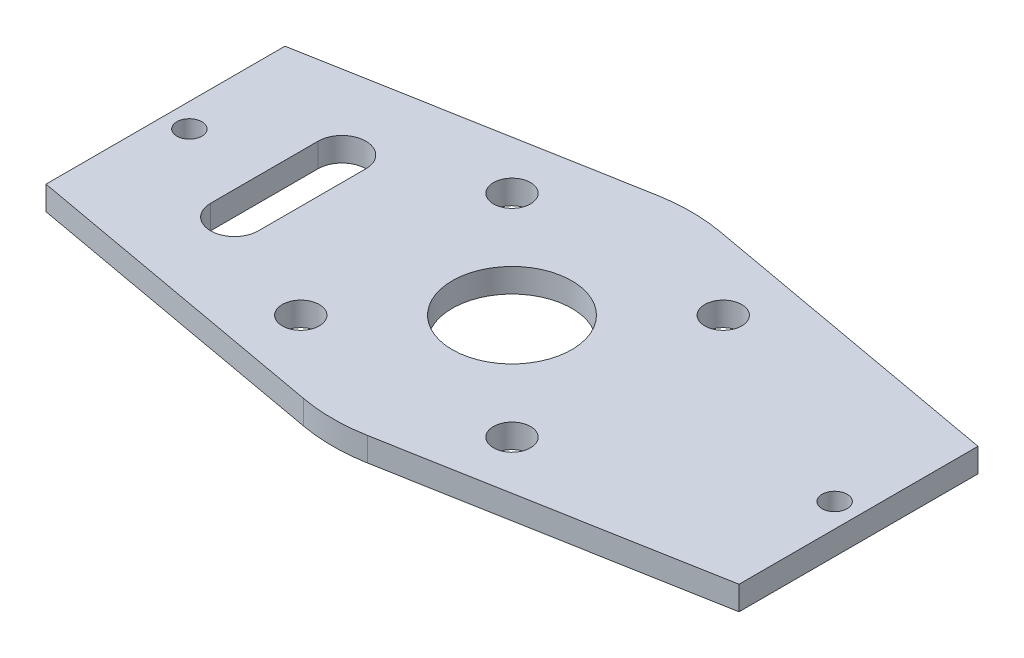
SolidWorks part; units mm, degrees
material "Hexcel AS4C (3000 Filaments)"
ref_plane "Front Plane" through (0, 0, 0) normal (0, 0, 1) x (1, 0, 0)
ref_plane "Top Plane" through (0, 0, 0) normal (0, 1, 0) x (1, 0, 0)
ref_plane "Right Plane" through (0, 0, 0) normal (1, 0, 0) x (0, 0, -1)
sketch "Sketch1" plane through (0, 0, 0) normal (0, 1, 0) x (1, 0, 0)
  line L0 (-2.6687, 14.7607) -> (-29, 10)
  line L1 (2.6687, 14.7607) -> (29, 10)
  line L2 (-2.6687, -14.7607) -> (-29, -10)
  line L4 (-29, 10) -> (-29, -10)
  line L11 (2.6687, -14.7607) -> (29, -10)
  line L12 (29, 10) -> (29, -10)
  line L14 (-18.7281, -4.5) -> (-18.7281, 4.5) construction
  line L15 (-20.7281, -4.5) -> (-20.7281, 4.5)
  line L16 (-16.7281, -4.5) -> (-16.7281, 4.5)
  circle A7 centre (0, 0) radius 5
  circle A8 centre (-27, 0) radius 1.05
  circle A9 centre (27, 0) radius 1.05
  circle A11 centre (8.8388, 8.8388) radius 1.55
  circle A12 centre (8.8388, -8.8388) radius 1.55
  circle A13 centre (-8.8388, -8.8388) radius 1.55
  circle A14 centre (-8.8388, 8.8388) radius 1.55
  arc A15 (-2.6687, 14.7607) -> (2.6687, 14.7607) centre (0, 0) cw
  arc A16 (2.6687, -14.7607) -> (-2.6687, -14.7607) centre (0, 0) cw
  arc A17 (-20.7281, -4.5) -> (-16.7281, -4.5) centre (-18.7281, -4.5) ccw
  arc A18 (-16.7281, 4.5) -> (-20.7281, 4.5) centre (-18.7281, 4.5) ccw
  point P12 (-18.7281, 0)
  point P15 (0, 0)
  point P33 (0, 0)
extrude "Boss-Extrude1" add sketch "Sketch1" along normal blind 2
